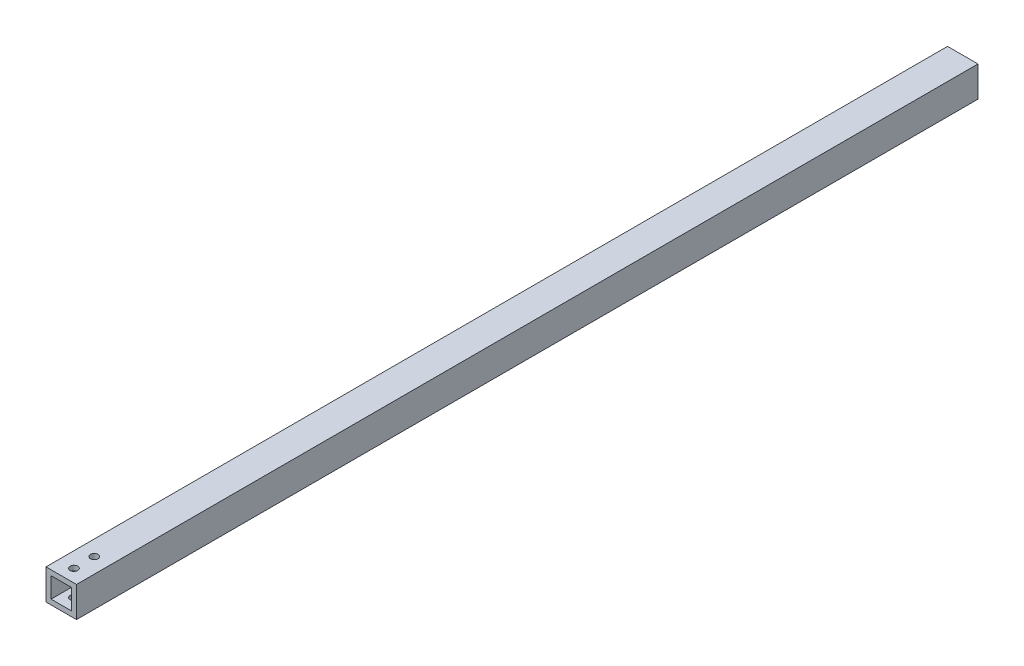
SolidWorks part; units mm, degrees
material "Thornel Mat VMA"
ref_plane "前视基准面" through (0, 0, 0) normal (0, 0, 1) x (1, 0, 0)
ref_plane "上视基准面" through (0, 0, 0) normal (0, 1, 0) x (1, 0, 0)
ref_plane "右视基准面" through (0, 0, 0) normal (1, 0, 0) x (0, 0, -1)
sketch "草图2" plane through (0, 0, 0) normal (0, 0, 1) x (1, 0, 0)
  line L1 (-6, 6) -> (6, 6)
  line L2 (-6, 6) -> (-6, -6)
  line L3 (-6, -6) -> (6, -6)
  line L4 (6, 6) -> (6, -6)
  line L5 (-6, 6) -> (6, -6) construction
  line L6 (-6, -6) -> (6, 6) construction
  line L7 (-4, 4) -> (4, 4)
  line L8 (-4, 4) -> (-4, -4)
  line L9 (-4, -4) -> (4, -4)
  line L10 (4, 4) -> (4, -4)
  line L11 (-4, 4) -> (4, -4) construction
  line L12 (-4, -4) -> (4, 4) construction
  point P0 (0, 0)
  point P2 (0, 0)
  dimension "D1" = 12
  dimension "D2" = 8
extrude "凸台-拉伸1" add sketch "草图2" along normal blind 355
sketch "草图3" plane through (-6, 0, 0) normal (-1, 0, 0) x (0, 0, 1)
  line L0 (355, 6) -> (355, -6) construction
  circle A0 centre (350, 0) radius 1.5
  circle A1 centre (342, 0) radius 1.5
  dimension "D1" = 3
  dimension "D2" = 3
  dimension "D3" = 8
  dimension "D4" = 5
sketch "草图5" plane through (0, 6, 0) normal (0, 1, 0) x (1, 0, 0)
  line L0 (0, -355) -> (0, -350) construction
  line L1 (6, -355) -> (-6, -355) construction
  line L2 (0, -350) -> (0, -342) construction
  circle A0 centre (0, -350) radius 1.5
  circle A1 centre (0, -342) radius 1.5
  dimension "D3" = 3
  dimension "D4" = 3
  dimension "D1" = 5
  dimension "D2" = 8
extrude "切除-拉伸2" cut sketch "草图5" against normal through all
